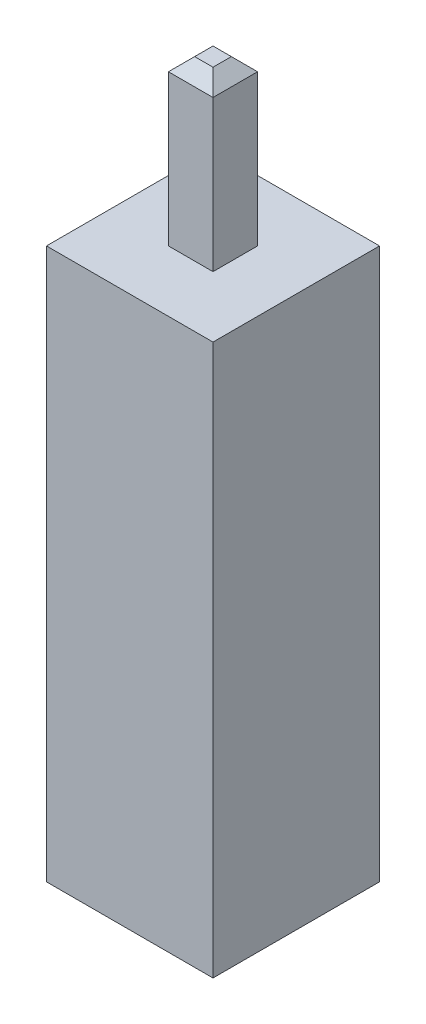
SolidWorks part; units mm, degrees
ref_plane "Front Plane" through (0, 0, 0) normal (0, 0, 1) x (1, 0, 0)
ref_plane "Top Plane" through (0, 0, 0) normal (0, 1, 0) x (1, 0, 0)
ref_plane "Right Plane" through (0, 0, 0) normal (1, 0, 0) x (0, 0, -1)
sketch "Sketch1" plane through (0, 0, 0) normal (0, 1, 0) x (1, 0, 0)
  line L1 (-0.34, -0.34) -> (0.34, -0.34)
  line L2 (-0.34, -0.34) -> (-0.34, 0.34)
  line L3 (-0.34, 0.34) -> (0.34, 0.34)
  line L4 (0.34, -0.34) -> (0.34, 0.34)
  line L5 (-0.34, -0.34) -> (0.34, 0.34) construction
  line L6 (-0.34, 0.34) -> (0.34, -0.34) construction
  line L7 (-1.27, -1.27) -> (1.27, -1.27)
  line L8 (-1.27, -1.27) -> (-1.27, 1.27)
  line L9 (-1.27, 1.27) -> (1.27, 1.27)
  line L10 (1.27, -1.27) -> (1.27, 1.27)
  line L11 (-1.27, -1.27) -> (1.27, 1.27) construction
  line L12 (-1.27, 1.27) -> (1.27, -1.27) construction
  point P0 (0, 0)
  point P6 (0, 0)
  dimension "D1" = 0.68
  dimension "D2" = 0.68
  dimension "D3" = 2.54
  dimension "D4" = 2.54
extrude "Boss-Extrude1" add sketch "Sketch1" along normal blind 8.4
sketch "Sketch2" plane through (0, 8.4, 0) normal (0, 1, 0) x (1, 0, 0)
  line L1 (-0.5, -0.5) -> (0.5, -0.5)
  line L2 (-0.5, -0.5) -> (-0.5, 0.5)
  line L3 (-0.5, 0.5) -> (0.5, 0.5)
  line L4 (0.5, -0.5) -> (0.5, 0.5)
  line L5 (-0.5, -0.5) -> (0.5, 0.5) construction
  line L6 (-0.5, 0.5) -> (0.5, -0.5) construction
  point P0 (0, 0)
  dimension "D1" = 1
  dimension "D2" = 1
extrude "Cut-Extrude1" cut sketch "Sketch2" against normal blind 7
chamfer "Chamfer1" distance 0.5 angle 45 4 edges at (0, 0, 0.34) (-0.34, 0, 0) (0.34, 0, 0) (0, 0, -0.34)
ref_plane "Plane1" through (0, 0, 0) normal (0, 0, 1) x (1, 0, 0)
sketch "Sketch4" plane through (0, 0, 0) normal (0, 0, 1) x (1, 0, 0)
  line L0 (-0.5, 1.4) -> (-0.34, 1.4)
  line L1 (-0.34, 1.4) -> (-0.34, 7.9006)
  line L4 (-0.5, 7.9006) -> (-0.5, 1.4)
  line L5 (0.5, 1.4) -> (0.34, 1.4)
  line L6 (-0.5, 1.4) -> (0.5, 1.4) construction
  line L7 (0.34, 1.4) -> (-0.34, 1.4) construction
  line L8 (0.34, 1.4) -> (0.34, 7.9006)
  line L10 (0.5, 7.9006) -> (0.5, 1.4)
  line L11 (-0.5, 8.4) -> (0.5, 8.4) construction
  line L12 (-0.5, 7.9006) -> (-0.34, 7.9006) construction
  line L13 (-0.5, 7.9006) -> (-0.34, 7.9006)
  line L14 (0.34, 7.9006) -> (0.5, 7.9006) construction
  line L15 (0.34, 7.9006) -> (0.5, 7.9006)
  dimension "D1" = 0.4994
extrude "Boss-Extrude2" add sketch "Sketch4" along normal up to surface (0.5 mm away) and the other way blind 0.5 contours L4 L0 L1 L13 | L10 L5 L8 L15 up to face at (0, 4.9, 0.5)
sketch "Sketch7" plane through (0, 7.9006, 0) normal (0, 1, 0) x (1, 0, 0)
  line L1 (-0.34, -0.34) -> (0.34, -0.34)
  line L2 (-0.34, -0.34) -> (-0.34, 0.34)
  line L3 (-0.34, 0.34) -> (0.34, 0.34)
  line L4 (0.34, -0.34) -> (0.34, 0.34)
  line L5 (-0.34, -0.34) -> (0.34, 0.34) construction
  line L6 (-0.34, 0.34) -> (0.34, -0.34) construction
  point P0 (0, 0)
extrude "Boss-Extrude3" add sketch "Sketch7" along normal blind 3 and the other way blind 1
sketch "Sketch8" plane through (0, 8.4, 0) normal (0, 1, 0) x (1, 0, 0)
  line L1 (-0.34, 0.34) -> (0.34, 0.34)
  line L2 (-0.34, 0.34) -> (-0.34, -0.34)
  line L3 (-0.34, -0.34) -> (0.34, -0.34)
  line L4 (0.34, 0.34) -> (0.34, -0.34)
  line L5 (-0.34, 0.34) -> (0.34, -0.34) construction
  line L6 (-0.34, -0.34) -> (0.34, 0.34) construction
  line L7 (-0.5, 0.5) -> (0.5, 0.5)
  line L8 (-0.5, 0.5) -> (-0.5, -0.5)
  line L9 (-0.5, -0.5) -> (0.5, -0.5)
  line L10 (0.5, 0.5) -> (0.5, -0.5)
  line L11 (-0.5, 0.5) -> (0.5, -0.5) construction
  line L12 (-0.5, -0.5) -> (0.5, 0.5) construction
  point P0 (0, 0)
  point P7 (0, 0)
extrude "Boss-Extrude4" add sketch "Sketch8" against normal up to surface (0.4994 mm away) up to face at (0.3933, 7.9006, 0)
chamfer "Chamfer2" distance 0.2 angle 45 4 edges at (0, 10.9006, -0.34) (0.34, 10.9006, 0) (-0.34, 10.9006, 0) (0, 10.9006, 0.34)
